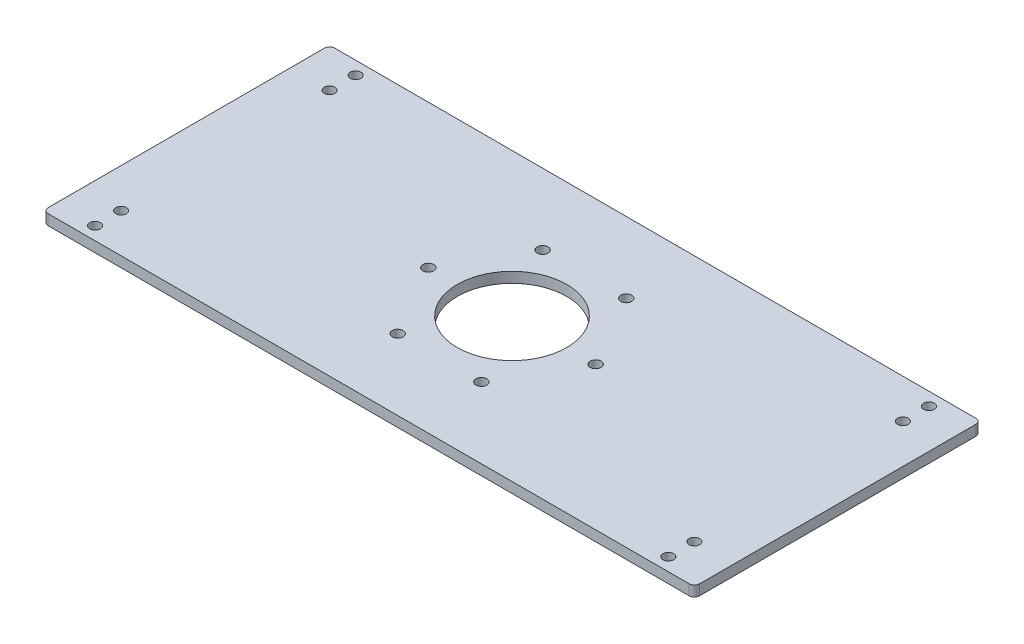
SolidWorks part; units mm, degrees
material "Thornel Mat VMA"
ref_plane "前视基准面" through (0, 0, 0) normal (0, 0, 1) x (1, 0, 0)
ref_plane "上视基准面" through (0, 0, 0) normal (0, 1, 0) x (1, 0, 0)
ref_plane "右视基准面" through (0, 0, 0) normal (1, 0, 0) x (0, 0, -1)
other "Configuration Table"
sketch "草图1" plane through (0, 0, 0) normal (0, 1, 0) x (1, 0, 0)
  line L1 (-125, 55) -> (125, 55)
  line L2 (-125, 55) -> (-125, -55)
  line L3 (-125, -55) -> (125, -55)
  line L4 (125, 55) -> (125, -55)
  line L5 (-125, 55) -> (125, -55) construction
  line L6 (-125, -55) -> (125, 55) construction
  point P0 (0, 0)
  dimension "D1" = 250
  dimension "D2" = 110
extrude "凸台-拉伸1" add sketch "草图1" along normal blind 4
sketch "草图3" plane through (0, 4, 0) normal (0, 1, 0) x (1, 0, 0)
  circle A0 centre (0, 0) radius 32.1 construction
  circle A1 centre (-32.1, 0) radius 2.1
  circle A2 centre (-16.05, 27.7994) radius 2.1
  circle A3 centre (16.05, 27.7994) radius 2.1
  circle A4 centre (32.1, 0) radius 2.1
  circle A5 centre (16.05, -27.7994) radius 2.1
  circle A6 centre (-16.05, -27.7994) radius 2.1
  point P18 (0, 0)
  dimension "D1" = 64.2
  dimension "D2" = 4.2
  dimension "D3" = 6
extrude "切除-拉伸1" cut sketch "草图3" against normal blind 10
sketch "草图4" plane through (0, 4, 0) normal (0, 1, 0) x (1, 0, 0)
  circle A0 centre (0, 0) radius 21
  dimension "D1" = 42
extrude "切除-拉伸2" cut sketch "草图4" against normal blind 10
sketch "草图5" plane through (0, 4, 0) normal (0, 1, 0) x (1, 0, 0)
  line L0 (-125, 55) -> (-125, -55) construction
  line L1 (-110, 50) -> (-110, 40) construction
  line L2 (125, 55) -> (-125, 55) construction
  line L3 (0, 55) -> (0, 45.7272) construction
  line L4 (-125, 0) -> (-107.5781, 0) construction
  circle A1 centre (-110, 50) radius 2.05
  circle A2 centre (-110, 40) radius 2.05
  circle A3 centre (110, 40) radius 2.05
  circle A4 centre (110, 50) radius 2.05
  circle A5 centre (110, -50) radius 2.05
  circle A6 centre (110, -40) radius 2.05
  circle A7 centre (-110, -50) radius 2.05
  circle A8 centre (-110, -40) radius 2.05
  point P8 (-110, 45)
  dimension "D1" = 4.1
  dimension "D2" = 10
  dimension "D3" = 15
  dimension "D4" = 10
extrude "切除-拉伸3" cut sketch "草图5" against normal blind 10
fillet "圆角1" radius 2 4 edges at (125, 2, -55) (125, 2, 55) (-125, 2, 55) (-125, 2, -55)
